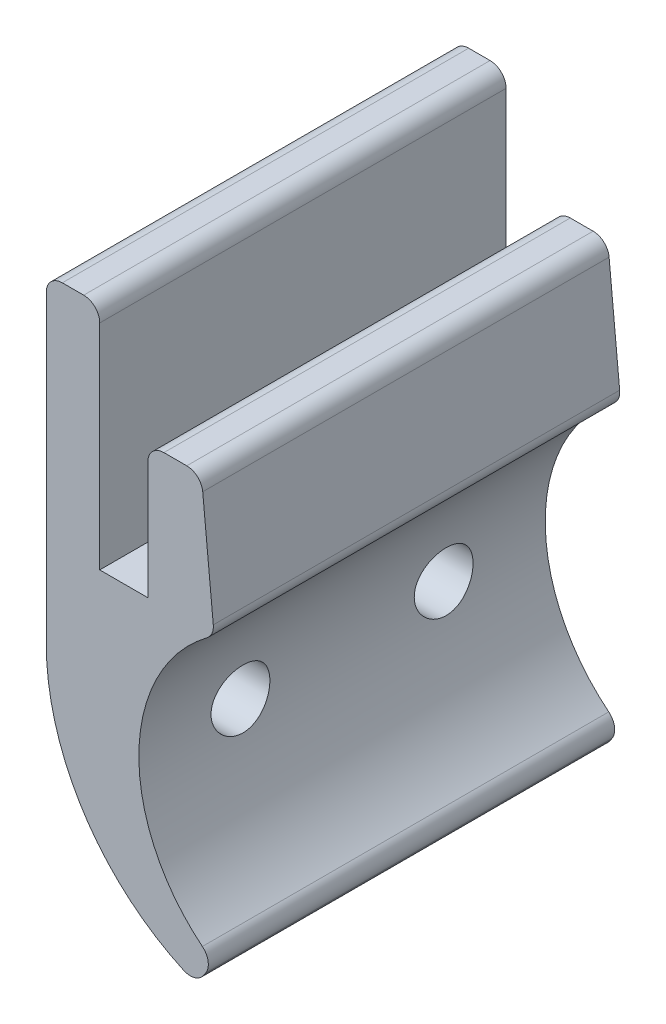
SolidWorks part; units mm, degrees
material "Ferro fundido cinza"
ref_plane "Plano frontal" through (0, 0, 0) normal (0, 0, 1) x (1, 0, 0)
ref_plane "Plano superior" through (0, 0, 0) normal (0, 1, 0) x (1, 0, 0)
ref_plane "Plano direito" through (0, 0, 0) normal (1, 0, 0) x (0, 0, -1)
sketch "Esboço1" plane through (0, 0, 0) normal (0, 0, 1) x (1, 0, 0)
  line L4 (0, 0) -> (0, -30)
  line L5 (0, 0) -> (5, 0)
  line L6 (5, 0) -> (5, -21.5)
  line L7 (5, -21.5) -> (9.5, -21.5)
  line L8 (9.5, -21.5) -> (9.5, -9)
  line L9 (9.5, -9) -> (14.5, -9)
  line L10 (14.5, -9) -> (15.7, -21.5)
  line L11 (14.0203, -50.5) -> (15.7, -48.0143)
  arc A0 (0, -30) -> (14.0203, -50.5) centre (21.9973, -30) ccw
  arc A1 (15.7, -48.0143) -> (15.7, -21.5) centre (24.6581, -34.7571) cw
  dimension "D1" = 5
  dimension "D9" = 16
  dimension "D2" = 5
  dimension "D3" = 4.5
  dimension "D4" = 15.7
  dimension "D5" = 21.5
  dimension "D6" = 12.5
  dimension "D7" = 50.5
  dimension "D8" = 30
  dimension "D10" = 3
extrude "Ressalto-extrusão1" add sketch "Esboço1" along normal mid plane 38
fillet "Filete1" radius 1.5 7 edges at (9.5, -9, 0) (15.7, -21.5, 0) (14.5, -9, 0) (5, 0, 0) (0, 0, 0) (15.7, -48.0143, 0) (14.0203, -50.5, 0)
sketch "Esboço3" plane through (0, 0, 0) normal (0, 0, 1) x (1, 0, 0)
  line L0 (0, -1.5) -> (-5, -6.5)
  line L1 (-5, -6.5) -> (-5, -24.5)
  line L2 (0, -1.5) -> (0, -30) construction
  line L3 (0, -1.5) -> (0, -30)
  arc A0 (-5, -24.5) -> (12.8438, -50.0024) centre (22.1459, -24.5) ccw
  arc A1 (0, -30) -> (12.8438, -50.0024) centre (21.9973, -30) ccw construction
  arc A2 (0, -30) -> (12.8438, -50.0024) centre (21.9973, -30) ccw
  dimension "D1" = 45
  dimension "D2" = 5
  dimension "D3" = 18
extrude "Ressalto-extrusão2" add sketch "Esboço3" along normal mid plane 5
hole_wizard "Rebaixo para parafuso Allen sextavado de M51" positions "Esboço4" profile "Esboço5" counterbore size "M5" standard "ISO" end condition through all
sketch "Esboço4" plane through (0, 0, 0) normal (-1, 0, 0) x (0, 0, 1)
  line L0 (0, 0) -> (0, -21.1991) construction
  line L1 (-19, 0) -> (19, 0) construction
  point P0 (-9.5, -34.75)
  point P2 (9.5, -34.75)
  dimension "D1" = 19
  dimension "D2" = 34.75
sketch "Esboço5" plane through (0, -34.75, -9.5) normal (0, 1, 0) x (0, 0, 1)
  line L0 (0, 0) -> (0, 15.6242)
  line L1 (0, 15.6242) -> (2.75, 15.6242)
  line L3 (2.75, 15.6242) -> (2.75, 3)
  line L4 (2.75, 3) -> (5.75, 3)
  line L5 (5.75, 3) -> (5.75, 0)
  line L7 (5.75, 0) -> (0, 0)
  line L11 (0, -6.35) -> (0, 107.95) construction
  dimension "Thru Hole Dia." = 5.5
  dimension "Thru Hole Depth" = 15.6242
  dimension "C'Bore Dia." = 11.5
  dimension "C'Bore Depth" = 3
